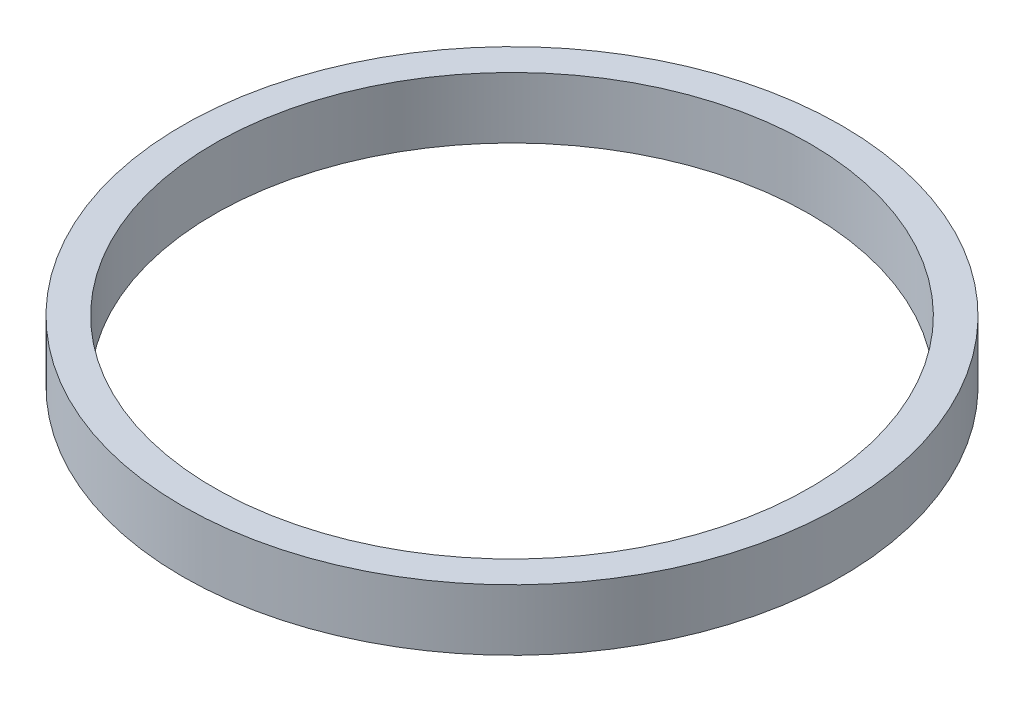
SolidWorks part; units mm, degrees
ref_plane "Front Plane" through (0, 0, 0) normal (0, 0, 1) x (1, 0, 0)
ref_plane "Top Plane" through (0, 0, 0) normal (0, 1, 0) x (1, 0, 0)
ref_plane "Right Plane" through (0, 0, 0) normal (1, 0, 0) x (0, 0, -1)
sketch "Sketch1" plane through (0, 0, 0) normal (0, 0, 1) x (1, 0, 0)
  line L0 (0, 0) -> (0, 6.0593) construction
  line L5 (-12.7, 2.6035) -> (-14.0462, 2.6035)
  line L9 (-12.7, 2.6035) -> (-12.7, 0)
  line L10 (-12.7, 0) -> (-14.0462, 0)
  line L11 (-14.0462, 0) -> (-14.0462, 2.6035)
  point P11 (-13.7595, 2.6035)
  dimension "D1" = 12.7
  dimension "D2" = 2.6035
  dimension "D8" = 14.0462
revolve "Revolve1" add sketch "Sketch1" angle 360 about L0
